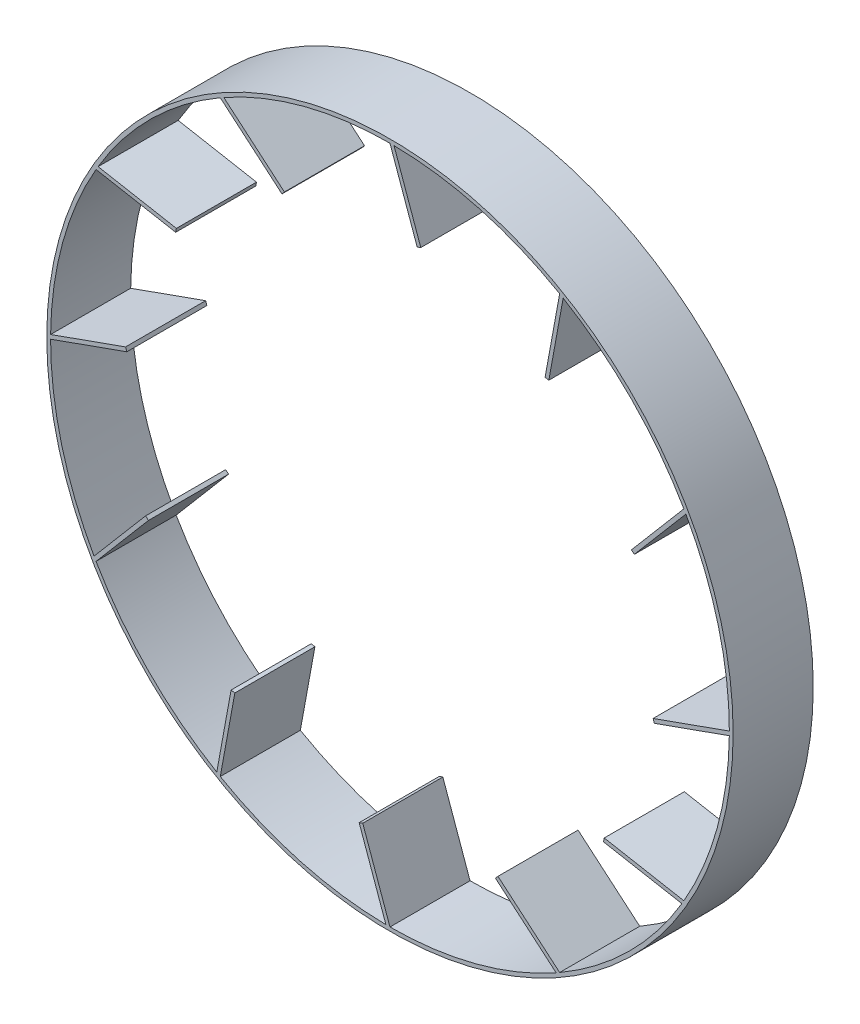
SolidWorks part; units mm, degrees
ref_plane "Front Plane" through (0, 0, 0) normal (0, 0, 1) x (1, 0, 0)
ref_plane "Top Plane" through (0, 0, 0) normal (0, 1, 0) x (1, 0, 0)
ref_plane "Right Plane" through (0, 0, 0) normal (1, 0, 0) x (0, 0, -1)
sketch "Sketch1" plane through (0, 0, 0) normal (0, 0, 1) x (1, 0, 0)
  circle A0 centre (0, 0) radius 226.06
  circle A1 centre (0, 0) radius 228.6
  dimension "D1" = 457.2
  dimension "D2" = 452.12
extrude "Boss-Extrude1" add sketch "Sketch1" along normal blind 53.34
sketch "Sketch2" plane through (0, 0, 53.34) normal (0, 0, 1) x (1, 0, 0)
  line L0 (0, 0) -> (-226.06, 0) construction
  line L1 (-226.06, 0) -> (-175.26, 18.1232)
  line L2 (-175.26, 18.1232) -> (-176.1135, 20.5155)
  line L3 (-176.1135, 20.5155) -> (-226.0438, 2.7026)
  line L4 (-195.7737, 113.03) -> (-142.718, 103.3252)
  line L5 (-142.718, 103.3252) -> (-142.261, 105.8237)
  line L6 (-142.261, 105.8237) -> (-194.4084, 115.3624)
  line L7 (-113.03, 195.7737) -> (-71.9348, 160.8412)
  line L8 (-71.9348, 160.8412) -> (-70.2898, 162.7765)
  line L9 (-70.2898, 162.7765) -> (-110.6814, 197.111)
  line L10 (0, 226.06) -> (18.1232, 175.26)
  line L11 (18.1232, 175.26) -> (20.5155, 176.1135)
  line L12 (20.5155, 176.1135) -> (2.7026, 226.0438)
  line L13 (113.03, 195.7737) -> (103.3252, 142.718)
  line L14 (103.3252, 142.718) -> (105.8237, 142.261)
  line L15 (105.8237, 142.261) -> (115.3624, 194.4084)
  line L16 (195.7737, 113.03) -> (160.8412, 71.9348)
  line L17 (160.8412, 71.9348) -> (162.7765, 70.2898)
  line L18 (162.7765, 70.2898) -> (197.111, 110.6814)
  line L19 (226.06, 0) -> (175.26, -18.1232)
  line L20 (175.26, -18.1232) -> (176.1135, -20.5155)
  line L21 (176.1135, -20.5155) -> (226.0438, -2.7026)
  line L22 (195.7737, -113.03) -> (142.718, -103.3252)
  line L23 (142.718, -103.3252) -> (142.261, -105.8237)
  line L24 (142.261, -105.8237) -> (194.4084, -115.3624)
  line L25 (113.03, -195.7737) -> (71.9348, -160.8412)
  line L26 (71.9348, -160.8412) -> (70.2898, -162.7765)
  line L27 (70.2898, -162.7765) -> (110.6814, -197.111)
  line L28 (0, -226.06) -> (-18.1232, -175.26)
  line L29 (-18.1232, -175.26) -> (-20.5155, -176.1135)
  line L30 (-20.5155, -176.1135) -> (-2.7026, -226.0438)
  line L31 (-113.03, -195.7737) -> (-103.3252, -142.718)
  line L32 (-103.3252, -142.718) -> (-105.8237, -142.261)
  line L33 (-105.8237, -142.261) -> (-115.3624, -194.4084)
  line L34 (-195.7737, -113.03) -> (-160.8412, -71.9348)
  line L35 (-160.8412, -71.9348) -> (-162.7765, -70.2898)
  line L36 (-162.7765, -70.2898) -> (-197.111, -110.6814)
  arc A1 (-226.0438, 2.7026) -> (-226.06, 0) centre (0, 0) ccw
  arc A2 (-194.4084, 115.3624) -> (-195.7737, 113.03) centre (0, 0) ccw
  arc A3 (-110.6814, 197.111) -> (-113.03, 195.7737) centre (0, 0) ccw
  arc A4 (2.7026, 226.0438) -> (0, 226.06) centre (0, 0) ccw
  arc A5 (115.3624, 194.4084) -> (113.03, 195.7737) centre (0, 0) ccw
  arc A6 (197.111, 110.6814) -> (195.7737, 113.03) centre (0, 0) ccw
  arc A7 (226.0438, -2.7026) -> (226.06, 0) centre (0, 0) ccw
  arc A8 (194.4084, -115.3624) -> (195.7737, -113.03) centre (0, 0) ccw
  arc A9 (110.6814, -197.111) -> (113.03, -195.7737) centre (0, 0) ccw
  arc A10 (-2.7026, -226.0438) -> (0, -226.06) centre (0, 0) ccw
  arc A11 (-115.3624, -194.4084) -> (-113.03, -195.7737) centre (0, 0) ccw
  arc A12 (-197.111, -110.6814) -> (-195.7737, -113.03) centre (0, 0) ccw
  dimension "D1" = 50.8
  dimension "D2" = 2.54
  dimension "D3" = 12
extrude "Boss-Extrude2" add sketch "Sketch2" against normal blind 53.34
